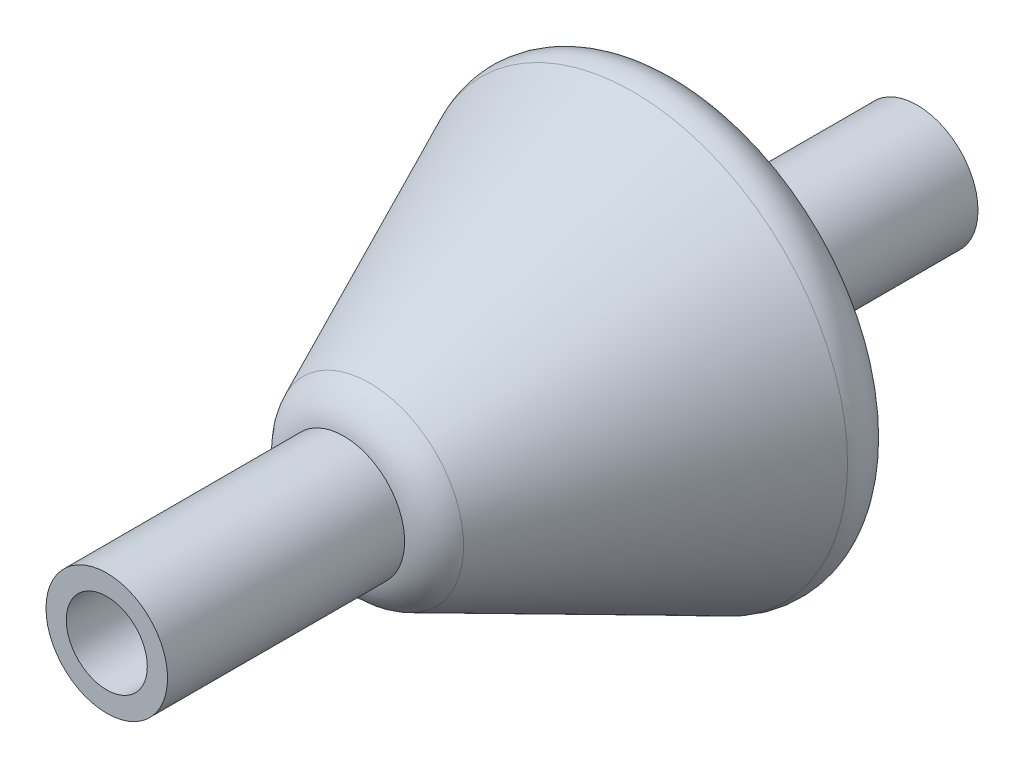
SolidWorks part; units mm, degrees
ref_plane "Front Plane" through (0, 0, 0) normal (0, 0, 1) x (1, 0, 0)
ref_plane "Top Plane" through (0, 0, 0) normal (0, 1, 0) x (1, 0, 0)
ref_plane "Right Plane" through (0, 0, 0) normal (1, 0, 0) x (0, 0, -1)
sketch "Sketch1" plane through (0, 0, 0) normal (0, 0, 1) x (1, 0, 0)
  circle A0 centre (0, 0) radius 6
  circle A1 centre (0, 0) radius 9
  dimension "D1" = 18
  dimension "D2" = 12
extrude "Boss-Extrude1" add sketch "Sketch1" along normal mid plane 120
sketch "Sketch2" plane through (0, 0, 0) normal (1, 0, 0) x (0, 0, -1)
  line L0 (-25, 0) -> (-25, 7.8403)
  line L1 (-21.0888, 13.929) -> (17.9211, 31.7636)
  line L2 (25, 27.2163) -> (25, 0)
  line L3 (25, 0) -> (-25, 0) construction
  line L4 (-25, 0) -> (25, 0)
  arc A1 (-25, 7.8403) -> (-21.0888, 13.929) centre (-18.3051, 7.8403) cw
  arc A2 (25, 27.2163) -> (17.9211, 31.7636) centre (20, 27.2163) ccw
  point P20 (25, 35)
  dimension "D1" = 50
  dimension "D2" = 5
  dimension "D3" = 35
revolve "Revolve1" add sketch "Sketch2" angle 360 about L3
